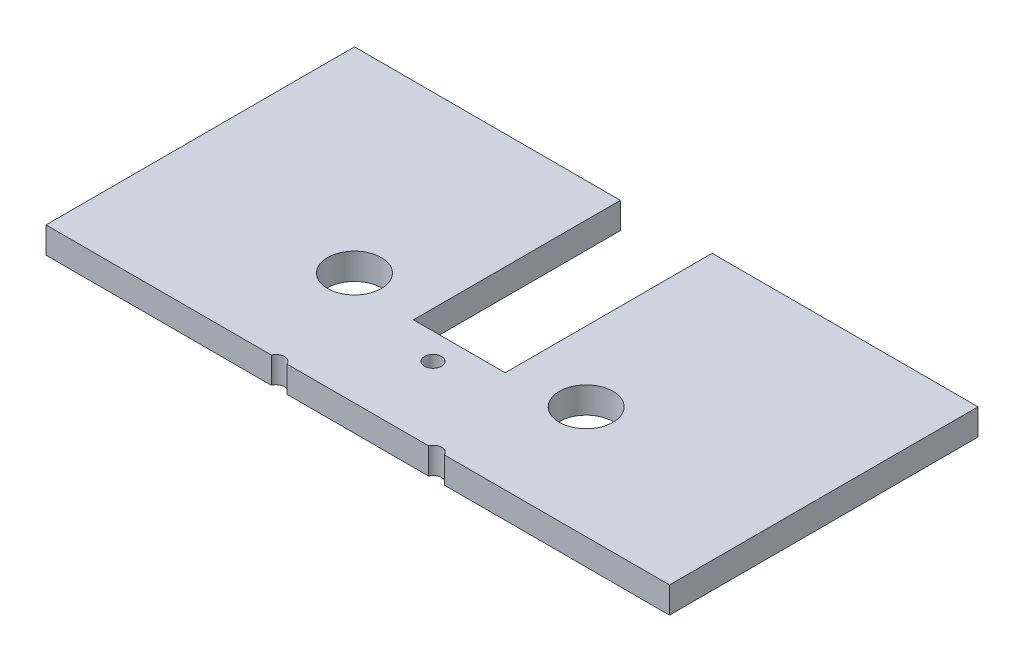
SolidWorks part; units mm, degrees
ref_plane "Front Plane" through (0, 0, 0) normal (0, 0, 1) x (1, 0, 0)
ref_plane "Top Plane" through (0, 0, 0) normal (0, 1, 0) x (1, 0, 0)
ref_plane "Right Plane" through (0, 0, 0) normal (1, 0, 0) x (0, 0, -1)
sketch "Sketch1" plane through (0, 0, 0) normal (0, 1, 0) x (1, 0, 0)
  line L0 (-3.5, 6.7693) -> (-3.5, 0.9807)
  line L1 (-13.7886, -6.7693) -> (13.7886, -6.7693)
  line L2 (-13.7886, -6.7693) -> (-13.7886, 6.7693)
  line L3 (-13.7886, 6.7693) -> (-3.5, 6.7693)
  line L4 (13.7886, -6.7693) -> (13.7886, 6.7693)
  line L5 (-13.7886, -6.7693) -> (13.7886, 6.7693) construction
  line L6 (-13.7886, 6.7693) -> (13.7886, -6.7693) construction
  line L7 (-3.5, 0.9807) -> (3.5, 0.9807)
  line L8 (3.5, 0.9807) -> (3.5, 6.7693)
  line L9 (3.5, 6.7693) -> (13.7886, 6.7693)
  line L10 (-3.5, 6.7693) -> (3.5, 6.7693) construction
  line L11 (-8.84, 1.8196) -> (8.84, 1.8196) construction
  circle A0 centre (-8.84, 1.8196) radius 2.05
  circle A1 centre (8.84, 1.8196) radius 2.05
  point P0 (0, 0)
  point P8 (0, 0.9807)
  point P15 (0, 1.8196)
  point P16 (0, 6.7693)
  dimension "D5" = 4.1
  dimension "D1" = 27.5772
  dimension "D2" = 13.5386
  dimension "D3" = 5.7886
  dimension "D4" = 7
  dimension "D6" = 4.9497
  dimension "D7" = 17.68
extrude "Boss-Extrude1" add sketch "Sketch1" along normal blind 2
sketch "Sketch3" plane through (0, 2, 0) normal (0, 1, 0) x (1, 0, 0)
  line L0 (-13.7886, -6.7693) -> (13.7886, -6.7693) construction
  line L1 (-13.7886, 6.7693) -> (-13.7886, -6.7693) construction
  circle A0 centre (-0.0086, -1.0193) radius 0.65
  dimension "D1" = 1.3
  dimension "D2" = 5.75
  dimension "D3" = 13.78
extrude "Cut-Extrude1" cut sketch "Sketch3" against normal through all
sketch "Sketch4" plane through (0, 2, 0) normal (0, 1, 0) x (1, 0, 0)
  line L0 (-13.7886, -6.7693) -> (13.7886, -6.7693) construction
  line L1 (3.5, 0.9807) -> (-3.5, 0.9807) construction
  line L2 (6, -7.0193) -> (-6, -7.0193) construction
  circle A0 centre (6, -7.0193) radius 0.65
  circle A1 centre (-6, -7.0193) radius 0.65
  point P6 (0, 0.9807)
  point P9 (0, -7.0193)
  dimension "D3" = 1.3
  dimension "D1" = 0.25
  dimension "D2" = 6
extrude "Cut-Extrude2" cut sketch "Sketch4" against normal through all
sketch "Sketch5" plane through (0, 2, 0) normal (0, 1, 0) x (1, 0, 0)
  line L0 (-13.7886, -6.7693) -> (-23.7886, -6.7693)
  line L1 (-13.7886, 6.7693) -> (-13.7886, -6.7693) construction
  line L2 (-23.7886, -6.7693) -> (-23.7886, 16.7693)
  line L3 (-23.7886, 16.7693) -> (-3.5, 16.7693)
  line L4 (-3.5, 16.7693) -> (-3.5, 6.7693)
  line L5 (3.5, 6.7693) -> (3.5, 16.7693)
  line L6 (3.5, 16.7693) -> (23.7886, 16.7693)
  line L7 (23.7886, 16.7693) -> (23.7886, -6.7693)
  line L8 (23.7886, -6.7693) -> (13.7886, -6.7693)
  line L9 (13.7886, -6.7693) -> (13.7886, 6.7693)
  line L10 (13.7886, 6.7693) -> (3.5, 6.7693)
  line L11 (-3.5, 6.7693) -> (-13.7886, 6.7693)
  line L12 (-3.5, 6.7693) -> (-13.7886, 6.7693) construction
  line L13 (-13.7886, 6.7693) -> (-13.7886, -6.7693)
  dimension "D1" = 10
  dimension "D2" = 10
extrude "Boss-Extrude2" add sketch "Sketch5" against normal up to surface (2 mm away) up to face at (-0.0086, 0, 1.6693)
